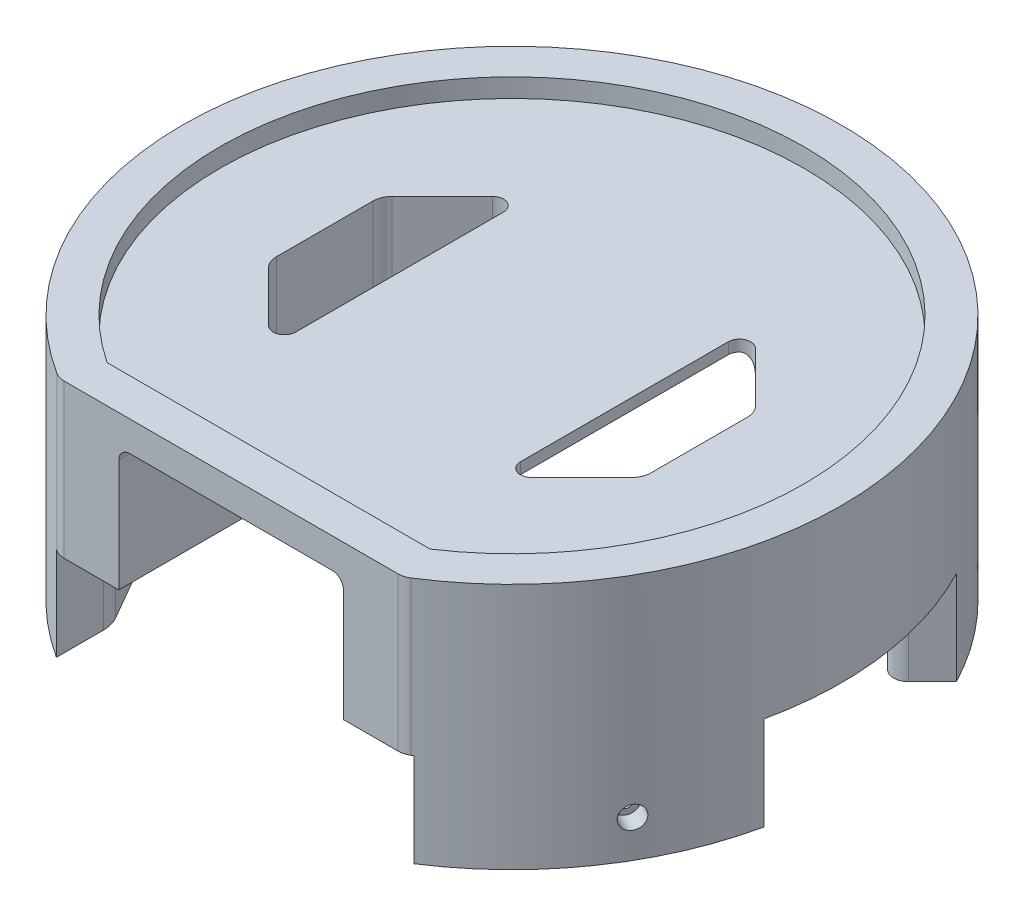
SolidWorks part; units mm, degrees
material "ABS"
ref_plane "Front Plane" through (0, 0, 0) normal (0, 0, 1) x (1, 0, 0)
ref_plane "Top Plane" through (0, 0, 0) normal (0, 1, 0) x (1, 0, 0)
ref_plane "Right Plane" through (0, 0, 0) normal (1, 0, 0) x (0, 0, -1)
sketch "Sketch1" plane through (0, 0, 0) normal (0, -1, 0) x (1, 0, 0)
  line L0 (0, 97.4246) -> (0, -108.8317) construction
  line L1 (-109.4364, 0) -> (110.4876, 0) construction
  line L2 (0, 0) -> (76.2102, 44) construction
  line L3 (0, 0) -> (62.2254, -62.2254) construction
  line L4 (0, 0) -> (-76.2102, 44) construction
  line L5 (0, 0) -> (-62.2254, -62.2254) construction
  circle A0 centre (0, 0) radius 88 construction
  dimension "D1" = 176
  dimension "D2" = 60
  dimension "D3" = 60
  dimension "D4" = 45
  dimension "D5" = 45
sketch "Sketch3" plane through (0, 0, 0) normal (0, 1, 0) x (1, 0, 0)
  line L0 (-46.0326, -75) -> (46.0326, -75)
  arc A0 (46.0326, -75) -> (-46.0326, -75) centre (0, 0) ccw
  circle A1 centre (0, 0) radius 88 construction
  dimension "D1" = 75
extrude "Boss-Extrude1" add sketch "Sketch3" along normal blind 66
sketch "Sketch2" plane through (0, 0, 0) normal (0, 1, 0) x (1, 0, 0)
  line L0 (31.4062, 68.8829) -> (68.8829, 31.4062)
  line L1 (-31.4062, 68.8829) -> (-68.8829, 31.4062)
  line L2 (74.7243, -12.2346) -> (47.7243, -59)
  line L3 (-74.7243, -12.2346) -> (-47.7243, -59)
  line L4 (0, 0) -> (-62.2254, 62.2254) construction
  line L5 (0, 0) -> (62.2254, 62.2254) construction
  line L6 (-46.0326, -75) -> (46.0326, -75) construction
  line L7 (0, 0) -> (76.2102, -44) construction
  line L8 (-68.8829, 31.4062) -> (-78.0753, 40.5986)
  line L9 (-31.4062, 68.8829) -> (-40.5986, 78.0753)
  line L10 (31.4062, 68.8829) -> (40.5986, 78.0753)
  line L11 (68.8829, 31.4062) -> (78.0753, 40.5986)
  line L12 (74.7243, -12.2346) -> (85.9826, -18.7346)
  line L13 (47.7243, -59) -> (47.7243, -75)
  line L14 (-74.7243, -12.2346) -> (-85.9826, -18.7346)
  line L15 (-47.7243, -59) -> (-47.7243, -75)
  line L16 (0, 0) -> (0, -124.9936) construction
  line L17 (-46.0326, -75) -> (-47.7243, -75)
  line L18 (47.7243, -75) -> (46.0326, -75)
  arc A0 (-40.5986, 78.0753) -> (40.5986, 78.0753) centre (0, 0) cw
  arc A1 (-46.0326, -75) -> (46.0326, -75) centre (0, 0) ccw
  arc A2 (78.0753, 40.5986) -> (85.9826, -18.7346) centre (0, 0) cw
  arc A3 (-78.0753, 40.5986) -> (-85.9826, -18.7346) centre (0, 0) ccw
  circle A4 centre (0, 0) radius 88
  point P2 (-72.2206, -21.5675)
  point P3 (50.1446, 50.1446)
  point P21 (-50.1446, 50.1446)
  dimension "D2" = 75
  dimension "D8" = 176
  dimension "D4" = 13
  dimension "D1" = 53
  dimension "D3" = 54
  dimension "D5" = 16
extrude "Cut-Extrude3" cut sketch "Sketch2" against normal blind 10 and the other way blind 25
fillet "Fillet1" radius 4 6 edges at (-74.7243, 12.5, 12.2346) (74.7243, 12.5, 12.2346) (68.8829, 12.5, -31.4062) (31.4062, 12.5, -68.8829) (-68.8829, 12.5, -31.4062) (-31.4062, 12.5, -68.8829)
fillet "Fillet3" radius 9 2 edges at (-47.7243, 12.5, 59) (47.7243, 12.5, 59)
fillet "Fillet4" [suppressed] radius 2
sketch "Sketch4" plane through (0, 25, 0) normal (0, -1, 0) x (1, 0, 0)
  line L0 (-46.0326, 75) -> (46.0326, 75) construction
  line L1 (-30, -75) -> (30, -75)
  line L2 (-30, -75) -> (-30, 75)
  line L3 (-30, 75) -> (30, 75)
  line L4 (30, -75) -> (30, 75)
  line L5 (-30, -75) -> (30, 75) construction
  line L6 (-30, 75) -> (30, -75) construction
  arc A0 (-30, -75) -> (30, -75) centre (0, 0) ccw
  point P0 (0, 0)
  point P8 (0, 0)
  dimension "D1" = 60
extrude "Cut-Extrude4" cut sketch "Sketch4" against normal blind 33
sketch "Sketch5" plane through (0, 66, 0) normal (0, 1, 0) x (1, 0, 0)
  line L2 (-43.1161, -65) -> (43.1161, -65)
  line L3 (-43.1161, -65) -> (43.1161, -65)
  arc A2 (43.1161, -65) -> (-43.1161, -65) centre (0, 0) ccw
  arc A3 (43.1161, -65) -> (-43.1161, -65) centre (0, 0) ccw
  dimension "D1" = 10
extrude "Cut-Extrude5" cut sketch "Sketch5" against normal blind 5
sketch "Sketch6" plane through (0, 25, 0) normal (0, -1, 0) x (1, 0, 0)
  line L0 (30, 35) -> (50, 15)
  line L1 (30, -75) -> (30, 75) construction
  line L2 (50, 15) -> (50, -15)
  line L3 (50, -15) -> (30, -35)
  line L4 (30, -75) -> (30, 75) construction
  line L5 (30, -35) -> (30, 35)
  line L6 (0, 80.1141) -> (0, -102.0682) construction
  line L8 (-50, -15) -> (-30, -35)
  line L9 (-50, 15) -> (-50, -15)
  line L11 (-30, -35) -> (-30, 35)
  line L12 (-30, 35) -> (-50, 15)
  point P10 (57.5, -5.6209)
  point P11 (30, 0)
  dimension "D1" = 20
  dimension "D2" = 30
extrude "Cut-Extrude6" cut sketch "Sketch6" against normal through all
fillet "Fillet5" radius 3 4 edges at (-30, 59.5, 35) (-30, 59.5, -35) (30, 59.5, -35) (30, 59.5, 35)
fillet "Fillet6" radius 5 8 edges at (30, 41.5, -35) (50, 43, -15) (50, 43, 15) (30, 41.5, 35) (-30, 41.5, 35) (-50, 43, 15) (-50, 43, -15) (-30, 41.5, -35)
fillet "Fillet7" radius 3 15 edges at (-33.2929, 58, -31.7071) (-30.3806, 58, -35.1577) (33.2929, 58, -31.7071) (30.3806, 58, -35.1577) (33.2929, 58, 31.7071) (30.3806, 58, 35.1577) (-33.2929, 58, 31.7071) (-30.3806, 58, 35.1577) (-30, 58, -56.0355) (30, 58, -56.0355) (30, 58, 56.0355) (-30, 58, 56.0355) (0, 58, -80.7775) (30, 41.5, -75) (-30, 41.5, -75)
sketch "Sketch7" plane through (50.1446, 0, -50.1446) normal (-0.7071, 0, 0.7071) x (0.7071, 0, 0.7071)
  line L0 (22.5, 0) -> (-22.5, 0) construction
  circle A0 centre (0, 10) radius 1.5
  point P4 (0, 0)
  point P5 (0, 0)
  dimension "D1" = 3
  dimension "D2" = 10
extrude "Cut-Extrude7" cut sketch "Sketch7" against normal through all
ref_plane "Plane2" through (58.6299, 0, -58.6299) normal (-0.7071, 0, 0.7071) x (0.7071, 0, 0.7071)
sketch "Sketch11" plane through (58.6299, 0, -58.6299) normal (-0.7071, 0, 0.7071) x (0.7071, 0, 0.7071)
  circle A0 centre (0, 10) radius 3
  dimension "D1" = 6
extrude "Cut-Extrude10" cut sketch "Sketch11" against normal through all
sketch "Sketch9" plane through (0, 0, 0) normal (0, -1, 0) x (1, 0, 0)
  line L0 (0, 0) -> (97.8194, 56.4761) construction
  line L1 (0, 0) -> (127.5638, 0) construction
  dimension "D1" = 30
ref_plane "Plane1" through (71.7333, 0, 41.4152) normal (-0.866, 0, -0.5) x (-0.5, 0, 0.866)
sketch "Sketch8" plane through (61.341, 0, 35.4152) normal (-0.866, 0, -0.5) x (-0.5, 0, 0.866)
  line L0 (24.8218, 0) -> (-22.7667, 0) construction
  line L1 (0, 0) -> (0, 25) construction
  line L2 (-22.7667, 25) -> (24.8218, 25) construction
  circle A0 centre (0, 10) radius 1.5
  point P4 (0, 25)
  point P8 (0, 0)
  dimension "D2" = 3
  dimension "D1" = 10
extrude "Cut-Extrude8" cut sketch "Sketch8" against normal through all
sketch "Sketch10" plane through (71.7333, 0, 41.4152) normal (-0.866, 0, -0.5) x (-0.5, 0, 0.866)
  circle A0 centre (0, 10) radius 3
  dimension "D1" = 6
extrude "Cut-Extrude9" cut sketch "Sketch10" against normal through all
mirror "Mirror1" about plane through (0, 0, 0) normal (1, 0, 0) of "Cut-Extrude9", "Cut-Extrude10", "Cut-Extrude7", "Cut-Extrude8"
fillet "Fillet10" radius 5 2 edges at (46.0326, 45.5, 75) (-46.0326, 45.5, 75)
